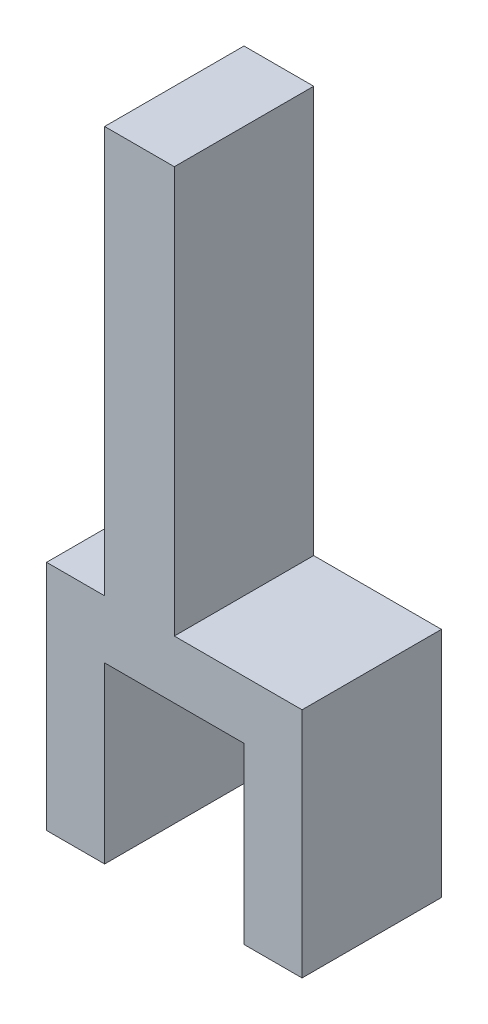
SolidWorks part; units mm, degrees
ref_plane "Спереди" through (0, 0, 0) normal (0, 0, 1) x (1, 0, 0)
ref_plane "Сверху" through (0, 0, 0) normal (0, 1, 0) x (1, 0, 0)
ref_plane "Справа" through (0, 0, 0) normal (1, 0, 0) x (0, 0, -1)
sketch "Эскиз1" plane through (0, 0, 0) normal (0, 0, 1) x (1, 0, 0)
  line L0 (0, 0) -> (96.1429, 0) construction
  line L1 (0, 0) -> (0, 58.7857) construction
  line L2 (0, 0) -> (5, 0)
  line L3 (5, 0) -> (5, 15)
  line L4 (5, 15) -> (17, 15)
  line L5 (17, 15) -> (17, 0)
  line L6 (17, 0) -> (22, 0)
  line L7 (22, 20) -> (11, 20)
  line L8 (11, 20) -> (11, 55)
  line L9 (11, 55) -> (5, 55)
  line L10 (5, 55) -> (5, 20)
  line L11 (5, 20) -> (0, 20)
  line L12 (0, 20) -> (0, 0)
  line L13 (22, 0) -> (22, 20)
  dimension "D1" = 12
  dimension "D2" = 5
  dimension "D3" = 5
  dimension "D4" = 20
  dimension "D5" = 15
  dimension "D6" = 11
  dimension "D7" = 20
  dimension "D8" = 35
extrude "Бобышка-Вытянуть1" add sketch "Эскиз1" along normal blind 12
